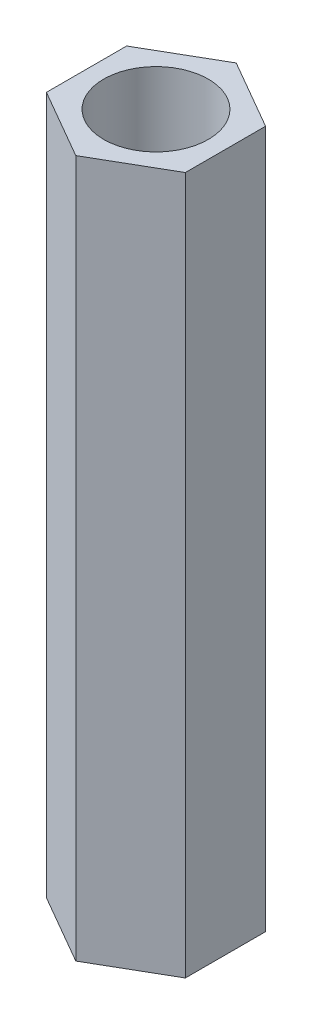
SolidWorks part; units mm, degrees
material "黄铜"
ref_plane "前视基准面" through (0, 0, 0) normal (0, 0, 1) x (1, 0, 0)
ref_plane "上视基准面" through (0, 0, 0) normal (0, 1, 0) x (1, 0, 0)
ref_plane "右视基准面" through (0, 0, 0) normal (1, 0, 0) x (0, 0, -1)
other "Configuration Table"
sketch "草图1" plane through (0, 0, 0) normal (0, 1, 0) x (1, 0, 0)
  line L1 (0, 2.3) -> (-1.9919, 1.15)
  line L2 (-1.9919, 1.15) -> (-1.9919, -1.15)
  line L3 (-1.9919, -1.15) -> (0, -2.3)
  line L4 (0, -2.3) -> (1.9919, -1.15)
  line L5 (1.9919, -1.15) -> (1.9919, 1.15)
  line L6 (1.9919, 1.15) -> (0, 2.3)
  circle A0 centre (0, 0) radius 1.5
  circle A1 centre (0, 0) radius 1.9919 construction
  dimension "D1" = 3
  dimension "D2" = 4.6
extrude "凸台-拉伸1" add sketch "草图1" along normal blind 20
